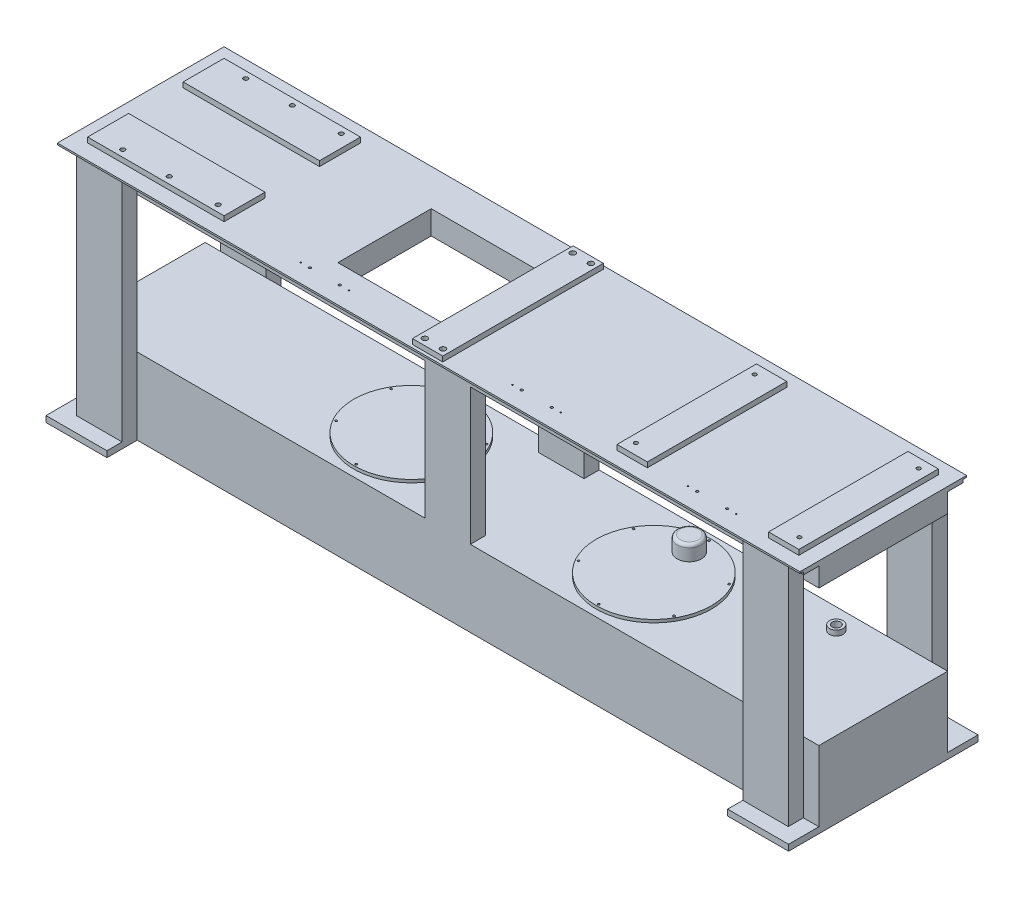
SolidWorks part; units mm, degrees
ref_plane "Front Plane" through (0, 0, 0) normal (0, 0, 1) x (1, 0, 0)
ref_plane "Top Plane" through (0, 0, 0) normal (0, 1, 0) x (1, 0, 0)
ref_plane "Right Plane" through (0, 0, 0) normal (1, 0, 0) x (0, 0, -1)
sketch "Sketch1" plane through (0, 0, 0) normal (0, 0, 1) x (1, 0, 0)
  line L1 (-1225, -390) -> (1225, -390)
  line L2 (-1225, -390) -> (-1225, 390)
  line L3 (-1225, 390) -> (1225, 390)
  line L4 (1225, -390) -> (1225, 390)
  line L5 (-1225, -390) -> (1225, 390) construction
  line L6 (-1225, 390) -> (1225, -390) construction
  point P0 (0, 0)
  dimension "D1" = 2450
  dimension "D2" = 780
extrude "Corpo" add sketch "Sketch1" against normal blind 625
sketch "Sketch3" plane through (0, 0, 0) normal (0, 0, 1) x (1, 0, 0)
  line L0 (1225, -390) -> (1225, 390) construction
  line L1 (1225, 384.4) -> (-1225, 384.4)
  line L2 (1225, 384.4) -> (1225, -370)
  line L3 (1225, -370) -> (-1225, -370)
  line L4 (-1225, 384.4) -> (-1225, -370)
  line L5 (-1225, -390) -> (1225, -390) construction
  line L6 (1225, 390) -> (-1225, 390) construction
  dimension "D1" = 20
  dimension "D2" = 5.6
  dimension "D3" = 2450
extrude "Corte dos Pés" cut sketch "Sketch3" against normal blind 50
ref_plane "Plano de Referência" through (0, 0, -312.5) normal (0, 0, 1) x (1, 0, 0)
mirror "Espelhamento - Corte dos Pés" about plane through (0, 0, -312.5) normal (0, 0, 1) of "Corte dos Pés"
sketch "Sketch4" plane through (1225, 0, 0) normal (1, 0, 0) x (0, 0, -1)
  line L0 (50, -370) -> (0, -370) construction
  line L1 (0, 375) -> (100, 375)
  line L2 (0, 375) -> (0, -370)
  line L3 (0, -370) -> (100, -370)
  line L4 (100, 375) -> (100, -370)
  line L6 (625, 390) -> (0, 390) construction
  dimension "D1" = 100
  dimension "D2" = 15
extrude "Corte Lateral" cut sketch "Sketch4" against normal blind 51
mirror "Espelhamento - Corte Lateral 1" about plane through (0, 0, -312.5) normal (0, 0, 1) of "Corte Lateral"
mirror "Espelhamento - Corte Lateral 2" about plane through (0, 0, 0) normal (1, 0, 0) of "Corte Lateral", "Espelhamento - Corte Lateral 1"
sketch "Sketch5" plane through (1225, 0, 0) normal (1, 0, 0) x (0, 0, -1)
  line L0 (312.5, 390) -> (312.5, -390) construction
  line L1 (625, 390) -> (0, 390) construction
  line L2 (625, -390) -> (0, -390) construction
  line L3 (0, -390) -> (0, -370) construction
  line L4 (100, -138) -> (525, -138)
  line L5 (100, -138) -> (100, 312)
  line L6 (100, 312) -> (525, 312)
  line L7 (525, -138) -> (525, 312)
  line L8 (100, -138) -> (525, 312) construction
  line L9 (100, 312) -> (525, -138) construction
  point P6 (312.5, 87)
  dimension "D1" = 252
  dimension "D2" = 100
  dimension "D3" = 450
extrude "Corte Interno" cut sketch "Sketch5" against normal through all
sketch "Sketch6" plane through (0, 0, -50) normal (0, 0, 1) x (1, 0, 0)
  line L0 (1225, 384.4) -> (-1225, 384.4) construction
  line L1 (1024, 384.4) -> (1174, 384.4)
  line L2 (1024, 384.4) -> (1024, -370)
  line L3 (1024, -370) -> (1174, -370)
  line L4 (1174, 384.4) -> (1174, -370)
  line L5 (-1174, -370) -> (1174, -370) construction
  line L6 (1174, 375) -> (1174, -370) construction
  line L7 (0, 384.4) -> (0, -370)
  line L8 (-1024, -370) -> (-1174, -370)
  line L9 (-1174, 384.4) -> (-1174, -370)
  line L10 (-1024, 384.4) -> (-1174, 384.4)
  line L11 (-1024, 384.4) -> (-1024, -370)
  line L13 (-1024, 384.4) -> (1024, 384.4)
  line L14 (-1024, 384.4) -> (-1024, -370)
  line L15 (-1024, -370) -> (1024, -370)
  line L16 (1024, 384.4) -> (1024, -370)
  line M16 (-1174, -370) -> (1174, -370)
  line M20 (1225, 384.4) -> (-1225, 384.4)
  dimension "D1" = 150
extrude "Corte das Pernas" cut sketch "Sketch6" against normal blind 50 contours L11 L7 M20 M16 | L7 L2 M20 M16
mirror "Espelhamento - Corte das Pernas" about plane through (0, 0, -312.5) normal (0, 0, 1) of "Corte das Pernas"
sketch "Sketch7" plane through (0, 0, -100) normal (0, 0, 1) x (1, 0, 0)
  line L0 (0, 312) -> (0, -138) construction
  line L1 (-1024, 312) -> (1024, 312) construction
  line L2 (1024, -138) -> (-1024, -138) construction
  line L4 (-75, -138) -> (75, -138)
  line L5 (-75, -138) -> (-75, 312)
  line L6 (-75, 312) -> (75, 312)
  line L7 (75, -138) -> (75, 312)
  line L8 (-75, -138) -> (75, 312) construction
  line L9 (-75, 312) -> (75, -138) construction
  point P6 (0, 87)
  dimension "D1" = 150
extrude "Coluna Central" add sketch "Sketch7" against normal blind 50
mirror "Espelhamento - Coluna Central" about plane through (0, 0, -312.5) normal (0, 0, 1) of "Coluna Central"
sketch "Sketch8" plane through (0, 390, 0) normal (0, 1, 0) x (1, 0, 0)
  line L0 (1126.5, 542.5) -> (1126.5, 82.5) construction
  line L2 (1076.5, 82.5) -> (1176.5, 82.5)
  line L3 (1076.5, 82.5) -> (1076.5, 542.5)
  line L4 (1076.5, 542.5) -> (1176.5, 542.5)
  line L5 (1176.5, 82.5) -> (1176.5, 542.5)
  line L6 (1076.5, 82.5) -> (1176.5, 542.5) construction
  line L7 (1076.5, 542.5) -> (1176.5, 82.5) construction
  line L9 (1225, 625) -> (1225, 0) construction
  line L10 (1225, 312.5) -> (1126.5, 312.5) construction
  line L21 (576.5, 82.5) -> (576.5, 542.5)
  line L22 (576.5, 82.5) -> (676.5, 82.5)
  line L23 (676.5, 82.5) -> (676.5, 542.5)
  line L24 (576.5, 542.5) -> (676.5, 542.5)
  line L25 (36.5, 312.5) -> (576.5, 312.5) construction
  line L26 (-63.5, 577.5) -> (36.5, 577.5)
  line L27 (-63.5, 577.5) -> (-63.5, 47.5)
  line L28 (-63.5, 47.5) -> (36.5, 47.5)
  line L29 (36.5, 577.5) -> (36.5, 47.5)
  line L30 (-63.5, 312.5) -> (-1225, 312.5) construction
  line L31 (-1175, 537.5) -> (-725, 537.5)
  line L32 (-1175, 537.5) -> (-1175, 402.5)
  line L33 (-1175, 402.5) -> (-725, 402.5)
  line L34 (-725, 537.5) -> (-725, 402.5)
  line L35 (-1225, 625) -> (-1225, 0) construction
  line L40 (-1175, 222.5) -> (-725, 222.5)
  line L41 (-725, 87.5) -> (-725, 222.5)
  line L42 (-1175, 87.5) -> (-725, 87.5)
  line L43 (-1175, 87.5) -> (-1175, 222.5)
  point P2 (1126.5, 312.5)
  dimension "D1" = 48.5
  dimension "D2" = 100
  dimension "D3" = 460
  dimension "D4" = 2
  dimension "D5" = 600
  dimension "D6" = 100
  dimension "D7" = 530
  dimension "D8" = 740
  dimension "D9" = 135
  dimension "D10" = 450
  dimension "D12" = 50
  dimension "D11" = 225
extrude "Resaltos da Mesa" add sketch "Sketch8" along normal blind 17
sketch "Sketch9" plane through (0, 390, 0) normal (0, 1, 0) x (1, 0, 0)
  line L0 (-247, 312.5) -> (-1225, 312.5) construction
  line L1 (-420.5, 158.5) -> (-73.5, 158.5)
  line L2 (-420.5, 158.5) -> (-420.5, 466.5)
  line L3 (-420.5, 466.5) -> (-73.5, 466.5)
  line L4 (-73.5, 158.5) -> (-73.5, 466.5)
  line L5 (-420.5, 158.5) -> (-73.5, 466.5) construction
  line L6 (-420.5, 466.5) -> (-73.5, 158.5) construction
  line L7 (-1225, 625) -> (-1225, 0) construction
  line L8 (-63.5, 577.5) -> (-63.5, 47.5) construction
  point P0 (-247, 312.5)
  dimension "D1" = 308
  dimension "D2" = 347
  dimension "D3" = 10
extrude "Rasgo 347x308" cut sketch "Sketch9" against normal up to next
sketch "Sketch16" plane through (0, 390, 0) normal (0, 1, 0) x (1, 0, 0)
  line L0 (-1225, 587.5) -> (1225, 587.5)
  line L1 (-1225, 0) -> (1225, 0)
  line L2 (-1225, 0) -> (-1225, 625)
  line L3 (-1225, 625) -> (1225, 625)
  line L4 (1225, 0) -> (1225, 625)
  line L5 (-1225, 37.5) -> (1225, 37.5)
  line M22 (-1225, 0) -> (1225, 0)
  line M23 (1225, 0) -> (1225, 625)
  line M24 (1225, 625) -> (-1225, 625)
  line M25 (-1225, 625) -> (-1225, 0)
  dimension "D1" = 37.5
  dimension "D2" = 37.5
extrude "Ajuste - Tamanho da Mesa" cut sketch "Sketch16" against normal up to next contours L5 L2 M22 M23 | L0 M25 M23 M24
sketch "Sketch18" plane through (0, 0, -525) normal (0, 0, -1) x (-1, 0, 0)
  line L0 (1024, 384.4) -> (1024, 312) construction
  line L1 (-1024, 384.4) -> (1024, 384.4)
  line L2 (-1024, 384.4) -> (-1024, 375)
  line L3 (-1024, 375) -> (1024, 375)
  line L4 (1024, 384.4) -> (1024, 375)
  line L5 (1225, 390) -> (-1225, 390) construction
  dimension "D1" = 15
extrude "Rebaixo da Mesa - Lado 1" add sketch "Sketch18" along normal up to surface (50 mm away) up to face at (1141, 129.8, -575)
sketch "Sketch38" plane through (0, 0, -100) normal (0, 0, 1) x (1, 0, 0)
  line L0 (1024, 384.4) -> (1024, 312) construction
  line L1 (-1024, 384.4) -> (1024, 384.4)
  line L2 (-1024, 384.4) -> (-1024, 375)
  line L3 (-1024, 375) -> (1024, 375)
  line L4 (1024, 384.4) -> (1024, 375)
  line L5 (-1225, 390) -> (1225, 390) construction
  dimension "D1" = 15
extrude "Rebaixo da Mesa - Lado 2" add sketch "Sketch38" along normal up to surface (50 mm away) up to face at (-1141, 129.8, -50)
sketch "Sketch11" plane through (0, 390, 0) normal (0, 1, 0) x (1, 0, 0)
  line L0 (796, 97.5) -> (826, 97.5) construction
  line L1 (826, 97.5) -> (925, 97.5) construction
  line L2 (925, 97.5) -> (955, 97.5) construction
  line L3 (1225, 587.5) -> (1225, 37.5) construction
  line L4 (1225, 0) -> (-1225, 0) construction
  line L5 (586, 0) -> (586, 97.5) construction
  line L6 (586, 97.5) -> (796, 97.5) construction
  line L7 (247, 97.5) -> (217, 97.5) construction
  line L8 (346, 97.5) -> (247, 97.5) construction
  line L9 (376, 97.5) -> (346, 97.5) construction
  line L10 (-53, 0) -> (-53, 97.5) construction
  line L11 (-53, 97.5) -> (217, 97.5) construction
  line L12 (-482, 97.5) -> (-452, 97.5) construction
  line L13 (-452, 97.5) -> (-353, 97.5) construction
  line L14 (-353, 97.5) -> (-323, 97.5) construction
  line L15 (-1225, 37.5) -> (1225, 37.5) construction
  circle A0 centre (826, 97.5) radius 4
  circle A1 centre (925, 97.5) radius 4
  circle A2 centre (955, 97.5) radius 2.425
  circle A3 centre (796, 97.5) radius 2.425
  circle A8 centre (376, 97.5) radius 2.425
  circle A9 centre (217, 97.5) radius 2.425
  circle A10 centre (247, 97.5) radius 4
  circle A11 centre (346, 97.5) radius 4
  circle A12 centre (-452, 97.5) radius 4
  circle A13 centre (-353, 97.5) radius 4
  circle A14 centre (-323, 97.5) radius 2.425
  circle A15 centre (-482, 97.5) radius 2.425
  dimension "D1" = 270
  dimension "D2" = 30
  dimension "D3" = 99
  dimension "D4" = 30
  dimension "D5" = 4.85
  dimension "D6" = 8
  dimension "D8" = 210
  dimension "D9" = 270
  dimension "D7" = 60
extrude "Furos dos Pinos - Ø8" cut sketch "Sketch11" against normal blind 30 contours A1 | A0 | A11 | A10 | A13 | A12
hole_wizard "Furos dos Contrapontos - M5" positions "Sketch12" profile "Sketch13" tap size "M5x0.8" standard "ANSI Metric"
sketch "Sketch12" plane through (0, 390, 0) normal (0, 1, 0) x (1, 0, 0)
  point P0 (955, 97.5)
  point P3 (796, 97.5)
  point P6 (376, 97.5)
  point P9 (217, 97.5)
  point P12 (-323, 97.5)
  point P15 (-482, 97.5)
sketch "Sketch13" plane through (955, 390, -97.5) normal (1, 0, 0) x (0, 0, 1)
  line L0 (0, 0) -> (0, 15)
  line L1 (0, 15) -> (2.1, 15)
  line L2 (2.1, 15) -> (2.1, 0)
  line L5 (2.1, 0) -> (0, 0)
  line L11 (0, -6.35) -> (0, 107.95) construction
  dimension "Thru Tap Drill Dia." = 4.2
  dimension "Thru Tap Drill Depth" = 15
cosmetic thread "Hole Thread1" parameters "D2"=5
cosmetic thread "Hole Thread2" parameters "D2"=5
cosmetic thread "Hole Thread3" parameters "D2"=5
cosmetic thread "Hole Thread4" parameters "D2"=5
cosmetic thread "Hole Thread5" parameters "D2"=5
cosmetic thread "Hole Thread6" parameters "D2"=5
sketch "Sketch17" plane through (0, -370, 0) normal (0, 1, 0) x (1, 0, 0)
  line L0 (-1225, 0) -> (1225, 0) construction
  line L1 (-1024, 100) -> (1024, 100)
  line L2 (-1024, 100) -> (-1024, 0)
  line L3 (-1024, 0) -> (1024, 0)
  line L4 (1024, 100) -> (1024, 0)
  line L5 (1024, 100) -> (1024, 50) construction
extrude "Corte do chão" cut sketch "Sketch17" against normal through all
mirror "Espelhamento - Corte do chão" about plane through (0, 0, -312.5) normal (0, 0, 1) of "Corte do chão"
sketch "Sketch19" plane through (0, 407, 0) normal (0, 1, 0) x (1, 0, 0)
  line L0 (1142.5, 511.5) -> (1142.5, 118) construction
  line L1 (1176.5, 542.5) -> (1076.5, 542.5) construction
  line L2 (1076.5, 82.5) -> (1176.5, 82.5) construction
  line L3 (1142.5, 118) -> (603.5, 118) construction
  line L4 (576.5, 542.5) -> (576.5, 82.5) construction
  line L5 (1176.5, 82.5) -> (1176.5, 542.5) construction
  line L6 (-43.55, 556.6) -> (16.35, 556.6) construction
  line L7 (603.5, 118) -> (603.5, 509.5) construction
  line L9 (676.5, 542.5) -> (576.5, 542.5) construction
  line L10 (-43.55, 68.4) -> (16.35, 68.4) construction
  line L11 (-13.6, 68.4) -> (-13.6, 556.6) construction
  line L12 (-950, 402.5) -> (-950, 222.5) construction
  line L13 (-1175, 402.5) -> (-725, 402.5) construction
  line L14 (36.5, 47.5) -> (36.5, 577.5) construction
  line L15 (-725, 222.5) -> (-1175, 222.5) construction
  line L16 (-950, 312.5) -> (-725, 312.5) construction
  line L17 (-725, 312.5) -> (-725, 402.5) construction
  line L18 (36.5, 577.5) -> (-63.5, 577.5) construction
  line L21 (-63.5, 47.5) -> (36.5, 47.5) construction
  line L22 (-1081.4, 515.5) -> (-927.9, 515.5) construction
  line L23 (-927.9, 515.5) -> (-766.4, 515.5) construction
  line L24 (-725, 537.5) -> (-1175, 537.5) construction
  line L27 (-725, 402.5) -> (-725, 537.5) construction
  line L28 (-927.9, 109.5) -> (-766.4, 109.5) construction
  line L29 (-1081.4, 109.5) -> (-927.9, 109.5) construction
  circle A0 centre (1142.5, 118) radius 7
  circle A1 centre (1142.5, 511.5) radius 7
  circle A2 centre (603.5, 118) radius 7
  circle A3 centre (603.5, 509.5) radius 7
  circle A4 centre (-43.55, 556.6) radius 8.9
  circle A5 centre (16.35, 556.6) radius 8.9
  circle A6 centre (-43.55, 68.4) radius 8.9
  circle A7 centre (16.35, 68.4) radius 8.9
  circle A8 centre (-1081.4, 515.5) radius 8
  circle A9 centre (-927.9, 515.5) radius 8
  circle A10 centre (-766.4, 515.5) radius 8
  circle A11 centre (-766.4, 109.5) radius 8
  circle A12 centre (-927.9, 109.5) radius 8
  circle A13 centre (-1081.4, 109.5) radius 8
  dimension "D1" = 31
  dimension "D2" = 35.5
  dimension "D3" = 27
  dimension "D4" = 14
  dimension "D6" = 33
  dimension "D7" = 11.25
  dimension "D8" = 77.7
  dimension "D9" = 12
  dimension "D10" = 12
  dimension "D11" = 17.8
  dimension "D12" = 14
  dimension "D13" = 33.4
  dimension "D14" = 145.5
  dimension "D15" = 145.5
  dimension "D16" = 16
  dimension "D5" = 27
extrude "Furos Passantes Centrais" cut sketch "Sketch19" against normal up to next contours A7 | A6 | A4 | A5
hole_wizard "Furos da Mesa - M14" positions "Sketch20" profile "Sketch21" tap size "M14x1.5" standard "ANSI Metric"
sketch "Sketch20" plane through (0, 407, 0) normal (0, 1, 0) x (1, 0, 0)
  point P0 (1142.5, 118)
  point P3 (1142.5, 511.5)
  point P6 (603.5, 509.5)
  point P9 (603.5, 118)
sketch "Sketch21" plane through (1142.5, 407, -118) normal (1, 0, 0) x (0, 0, 1)
  line L0 (0, 0) -> (0, 95)
  line L1 (0, 95) -> (6.25, 95)
  line L2 (6.25, 95) -> (6.25, 0)
  line L5 (6.25, 0) -> (0, 0)
  line L11 (0, -6.35) -> (0, 107.95) construction
  dimension "Thru Tap Drill Dia." = 12.5
  dimension "Thru Tap Drill Depth" = 95
cosmetic thread "Hole Thread7" parameters "D2"=14
cosmetic thread "Hole Thread8" parameters "D2"=14
cosmetic thread "Hole Thread9" parameters "D2"=14
cosmetic thread "Hole Thread10" parameters "D2"=14
hole_wizard "Furos da Mesa - M16" positions "Sketch22" profile "Sketch23" tap size "M16x1.5" standard "ANSI Metric"
sketch "Sketch22" plane through (0, 407, 0) normal (0, 1, 0) x (1, 0, 0)
  point P0 (-766.4, 515.5)
  point P3 (-927.9, 515.5)
  point P6 (-1081.4, 515.5)
  point P9 (-1081.4, 109.5)
  point P12 (-927.9, 109.5)
  point P15 (-766.4, 109.5)
sketch "Sketch23" plane through (-766.4, 407, -515.5) normal (1, 0, 0) x (0, 0, 1)
  line L0 (0, 0) -> (0, 95)
  line L1 (0, 95) -> (7.25, 95)
  line L2 (7.25, 95) -> (7.25, 0)
  line L5 (7.25, 0) -> (0, 0)
  line L11 (0, -6.35) -> (0, 107.95) construction
  dimension "Thru Tap Drill Dia." = 14.5
  dimension "Thru Tap Drill Depth" = 95
cosmetic thread "Hole Thread11" parameters "D2"=16
cosmetic thread "Hole Thread12" parameters "D2"=16
cosmetic thread "Hole Thread13" parameters "D2"=16
cosmetic thread "Hole Thread14" parameters "D2"=16
cosmetic thread "Hole Thread15" parameters "D2"=16
cosmetic thread "Hole Thread16" parameters "D2"=16
sketch "Sketch26" plane through (0, -138, 0) normal (0, 1, 0) x (1, 0, 0)
  line L0 (1225, 100) -> (1225, 525) construction
  line L2 (75, 525) -> (1024, 525) construction
  circle A0 centre (925, 457.5) radius 22.5
  dimension "D1" = 45
  dimension "D2" = 300
  dimension "D3" = 45
extrude "Encaixe do Cano da Base" add sketch "Sketch26" along normal blind 17
hole_wizard "Furo do Cano da Base - M30" positions "Sketch27" profile "Sketch28" tap size "M30x2.0" standard "ANSI Metric"
sketch "Sketch27" plane through (0, -121, 0) normal (0, 1, 0) x (1, 0, 0)
  point P0 (925, 457.5)
cosmetic thread "Hole Thread17" parameters "D1"=269, "D2"=30
sketch "Sketch28" plane through (925, -121, -457.5) normal (1, 0, 0) x (0, 0, 1)
  line L0 (0, 0) -> (0, 38.412)
  line L1 (0, 38.412) -> (14, 30)
  line L2 (14, 30) -> (14, 0)
  line L5 (14, 0) -> (0, 0)
  line L10 (0, 38.412) -> (-14, 30) construction
  line L11 (0, -6.35) -> (0, 107.95) construction
  dimension "Tap Drill Dia." = 28
  dimension "Tap Drill Depth" = 30
  dimension "Drill Angle" = 118
sketch "Sketch29" plane through (0, -138, 0) normal (0, 1, 0) x (1, 0, 0)
  line L0 (75, 475) -> (75, 525) construction
  line L1 (1225, 312.5) -> (468, 312.5) construction
  line L2 (1225, 100) -> (1225, 525) construction
  line L3 (468, 312.5) -> (-332, 312.5) construction
  circle A0 centre (468, 312.5) radius 190
  circle A1 centre (-332, 312.5) radius 190
  dimension "D1" = 380
  dimension "D2" = 393
  dimension "D3" = 420
extrude "Ressaltos da Base" add sketch "Sketch29" along normal blind 10
sketch "Posição dos Furos dos Ressaltos" plane through (0, -128, 0) normal (0, 1, 0) x (1, 0, 0)
  line L0 (468, 312.5) -> (468, 494.5) construction
  line L2 (278, 312.5) -> (-142, 312.5) construction
  line L3 (68, 312.5) -> (68, 475) construction
  line L4 (-75, 475) -> (75, 475) construction
  circle A0 centre (468, 312.5) radius 182 construction
  circle A1 centre (468, 494.5) radius 4
  circle A2 centre (625.6166, 403.5) radius 4
  circle A3 centre (625.6166, 221.5) radius 4
  circle A4 centre (468, 130.5) radius 4
  circle A5 centre (310.3834, 221.5) radius 4
  circle A6 centre (310.3834, 403.5) radius 4
  circle A7 centre (468, 312.5) radius 190 construction
  circle A8 centre (-332, 312.5) radius 190 construction
  circle A9 centre (625.6166, 403.5) radius 4
  circle A10 centre (625.6166, 221.5) radius 4
  circle A11 centre (310.3834, 221.5) radius 4
  circle A12 centre (310.3834, 403.5) radius 4
  circle A13 centre (625.6166, 403.5) radius 4
  circle A14 centre (625.6166, 221.5) radius 4
  circle A15 centre (310.3834, 221.5) radius 4
  circle A16 centre (310.3834, 403.5) radius 4
  circle A17 centre (625.6166, 403.5) radius 4
  circle A18 centre (625.6166, 221.5) radius 4
  circle A19 centre (310.3834, 221.5) radius 4
  circle A20 centre (310.3834, 403.5) radius 4
  circle A21 centre (-332, 312.5) radius 182 construction
  circle A22 centre (-174.3834, 403.5) radius 4
  circle A23 centre (-174.3834, 221.5) radius 4
  circle A24 centre (-489.6166, 221.5) radius 4
  circle A25 centre (-489.6166, 403.5) radius 4
  circle A26 centre (-174.3834, 403.5) radius 4
  circle A27 centre (-174.3834, 221.5) radius 4
  circle A28 centre (-489.6166, 221.5) radius 4
  circle A29 centre (-489.6166, 403.5) radius 4
  circle A30 centre (-174.3834, 403.5) radius 4
  circle A31 centre (-174.3834, 221.5) radius 4
  circle A32 centre (-489.6166, 221.5) radius 4
  circle A33 centre (-489.6166, 403.5) radius 4
  circle A34 centre (-174.3834, 403.5) radius 4
  circle A35 centre (-174.3834, 221.5) radius 4
  circle A36 centre (-332, 130.5) radius 4
  circle A37 centre (-489.6166, 221.5) radius 4
  circle A38 centre (-489.6166, 403.5) radius 4
  circle A39 centre (-332, 494.5) radius 4
  point P18 (468, 312.5)
  point P66 (-332, 312.5)
  dimension "D1" = 364
  dimension "D2" = 8
  dimension "D3" = 6
hole_wizard "Furos dos Ressaltos - M8" positions "Sketch35" profile "Sketch36" tap size "M8x1.0" standard "ANSI Metric"
sketch "Sketch35" plane through (0, -128, 0) normal (0, 1, 0) x (1, 0, 0)
  point P0 (468, 494.5)
  point P3 (625.6166, 403.5)
  point P6 (625.6166, 221.5)
  point P9 (468, 130.5)
  point P12 (310.3834, 221.5)
  point P15 (310.3834, 403.5)
  point P19 (-332, 494.5)
  point P22 (-174.3834, 403.5)
  point P25 (-174.3834, 221.5)
  point P28 (-332, 130.5)
  point P31 (-489.6166, 221.5)
  point P34 (-489.6166, 403.5)
sketch "Sketch36" plane through (468, -128, -494.5) normal (1, 0, 0) x (0, 0, 1)
  line L0 (0, 0) -> (0, 32.103)
  line L1 (0, 32.103) -> (3.5, 30)
  line L2 (3.5, 30) -> (3.5, 0)
  line L5 (3.5, 0) -> (0, 0)
  line L10 (0, 32.103) -> (-3.5, 30) construction
  line L11 (0, -6.35) -> (0, 107.95) construction
  dimension "Tap Drill Dia." = 7
  dimension "Tap Drill Depth" = 30
  dimension "Drill Angle" = 118
cosmetic thread "Hole Thread18" parameters "D1"=16, "D2"=8
cosmetic thread "Hole Thread19" parameters "D1"=16, "D2"=8
cosmetic thread "Hole Thread20" parameters "D1"=16, "D2"=8
cosmetic thread "Hole Thread21" parameters "D1"=16, "D2"=8
cosmetic thread "Hole Thread22" parameters "D1"=16, "D2"=8
cosmetic thread "Hole Thread23" parameters "D1"=16, "D2"=8
cosmetic thread "Hole Thread24" parameters "D1"=16, "D2"=8
cosmetic thread "Hole Thread25" parameters "D1"=16, "D2"=8
cosmetic thread "Hole Thread26" parameters "D1"=16, "D2"=8
cosmetic thread "Hole Thread27" parameters "D1"=16, "D2"=8
cosmetic thread "Hole Thread28" parameters "D1"=16, "D2"=8
cosmetic thread "Hole Thread29" parameters "D1"=16, "D2"=8
sketch "Sketch37" plane through (0, -128, 0) normal (0, 1, 0) x (1, 0, 0)
  line L0 (468, 429.5) -> (468, 494.5) construction
  circle A0 centre (468, 429.5) radius 40
  circle A5 centre (468, 312.5) radius 190 construction
  dimension "D1" = 80
  dimension "D2" = 33
extrude "Tampa do Ressalto" add sketch "Sketch37" along normal blind 50
fillet "Arredondamento da Tampa" radius 10 1 edges at (468, -78, -389.5)
